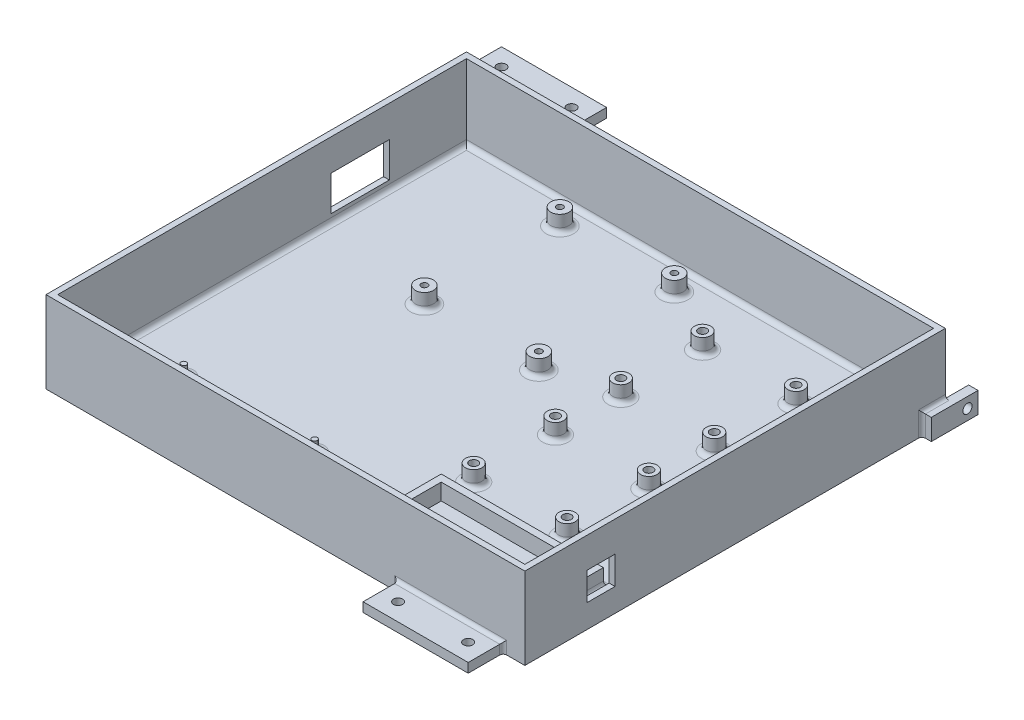
SolidWorks part; units mm, degrees
ref_plane "Front Plane" through (0, 0, 0) normal (0, 0, 1) x (1, 0, 0)
ref_plane "Top Plane" through (0, 0, 0) normal (0, 1, 0) x (1, 0, 0)
ref_plane "Right Plane" through (0, 0, 0) normal (1, 0, 0) x (0, 0, -1)
other "Configuration Table"
sketch "Sketch1" plane through (0, 0, 0) normal (0, 1, 0) x (1, 0, 0)
  line L1 (100, -87.5) -> (-100, -87.5)
  line L2 (100, -87.5) -> (100, 87.5)
  line L3 (100, 87.5) -> (-100, 87.5)
  line L4 (-100, -87.5) -> (-100, 87.5)
  line L5 (100, -87.5) -> (-100, 87.5) construction
  line L6 (100, 87.5) -> (-100, -87.5) construction
  point P0 (0, 0)
  dimension "D1" = 175
  dimension "D2" = 200
extrude "Boss-Extrude1" add sketch "Sketch1" along normal blind 3
sketch "Sketch2" plane through (0, 3, 0) normal (0, 1, 0) x (1, 0, 0)
  line L0 (-100, -87.5) -> (100, -87.5) construction
  line L1 (26.6, -49.9) -> (90, -49.9)
  line L2 (26.6, -49.9) -> (26.6, -77.5)
  line L3 (26.6, -77.5) -> (90, -77.5)
  line L4 (90, -49.9) -> (90, -77.5)
  line L5 (26.6, -49.9) -> (90, -77.5) construction
  line L6 (26.6, -77.5) -> (90, -49.9) construction
  line L7 (100, -87.5) -> (100, 87.5) construction
  line L8 (23.6, -46.9) -> (23.6, -80.5)
  line L9 (23.6, -80.5) -> (93, -80.5)
  line L10 (93, -46.9) -> (93, -80.5)
  line L11 (23.6, -46.9) -> (93, -46.9)
  point P0 (58.3, -63.7)
  dimension "D1" = 27.6
  dimension "D2" = 63.4
  dimension "D3" = 10
  dimension "D4" = 10
  dimension "D5" = 3
extrude "Boss-Extrude2" add sketch "Sketch2" along normal blind 7
sketch "Sketch3" plane through (0, 3, 0) normal (0, 1, 0) x (1, 0, 0)
  line L0 (26.5, -0.9) -> (66.5, -35.9) construction
  line L1 (26.5, -35.9) -> (66.5, -0.9) construction
  line L3 (70, -39.9) -> (23, -39.9) construction
  line L4 (70, -39.9) -> (70, 3.1) construction
  line L5 (70, 3.1) -> (23, 3.1) construction
  line L6 (23, -39.9) -> (23, 3.1) construction
  line L7 (70, -39.9) -> (23, 3.1) construction
  line L8 (70, 3.1) -> (23, -39.9) construction
  line L9 (100, -87.5) -> (100, 87.5) construction
  line L10 (100, 13.1) -> (-23, 13.1) construction
  line L11 (93, -46.9) -> (23.6, -46.9) construction
  circle A0 centre (26.5, -35.9) radius 1.8182
  circle A1 centre (66.5, -35.9) radius 1.8182
  circle A2 centre (66.5, -0.9) radius 1.8182
  circle A3 centre (26.5, -0.9) radius 1.8182
  circle A4 centre (26.5, -0.9) radius 3.5
  circle A5 centre (26.5, -35.9) radius 3.5
  circle A6 centre (66.5, -0.9) radius 3.5
  circle A7 centre (66.5, -35.9) radius 3.5
  circle A8 centre (66.5, 27.1) radius 3.5
  circle A9 centre (66.5, 27.1) radius 1.8182
  circle A10 centre (26.5, 62.1) radius 1.8182
  circle A11 centre (66.5, 62.1) radius 3.5
  circle A12 centre (66.5, 62.1) radius 1.8182
  circle A13 centre (26.5, 62.1) radius 3.5
  circle A14 centre (26.5, 27.1) radius 1.8182
  circle A15 centre (26.5, 27.1) radius 3.5
  point P8 (46.5, -18.4)
  dimension "D1" = 3.6364
  dimension "D3" = 35
  dimension "D2" = 40
  dimension "D4" = 47
  dimension "D5" = 43
  dimension "D6" = 30
  dimension "D7" = 10
  dimension "D8" = 7
extrude "Boss-Extrude3" add sketch "Sketch3" along normal blind 7
sketch "Sketch4" plane through (0, 3, 0) normal (0, 1, 0) x (1, 0, 0)
  line L0 (-100, 87.5) -> (-100, -87.5) construction
  line L1 (100, 87.5) -> (-100, 87.5) construction
  circle A0 centre (-50, 77.5) radius 1.3636
  circle A1 centre (-1, 77.5) radius 1.3636
  circle A2 centre (-1, 19.5) radius 1.3636
  circle A3 centre (-50, 19.5) radius 1.3636
  circle A4 centre (-50, 77.5) radius 3.8636
  circle A5 centre (-1, 77.5) radius 3.8636
  circle A6 centre (-1, 19.5) radius 3.8636
  circle A7 centre (-50, 19.5) radius 3.8636
  point P24 (26.5, 77.5)
  dimension "D1" = 2.7273
  dimension "D2" = 58
  dimension "D3" = 49
  dimension "D5" = 50
  dimension "D6" = 10
  dimension "D4" = 2.5
extrude "Boss-Extrude4" add sketch "Sketch4" along normal blind 7
sketch "Sketch6" plane through (0, 0, 0) normal (0, -1, 0) x (1, 0, 0)
  line L4 (-100, 87.5) -> (-100, -87.5)
  line L5 (-100, -87.5) -> (100, -87.5)
  line L6 (100, -87.5) -> (100, 87.5)
  line L7 (100, 87.5) -> (-100, 87.5)
  line L8 (-100, 87.5) -> (-100, -87.5)
  line L9 (-100, -87.5) -> (100, -87.5)
  line L10 (100, -87.5) -> (100, 87.5)
  line L11 (100, 87.5) -> (-100, 87.5)
  line L16 (-102.5, 90) -> (-102.5, -90)
  line L17 (-102.5, -90) -> (102.5, -90)
  line L18 (102.5, -90) -> (102.5, 90)
  line L19 (102.5, 90) -> (-102.5, 90)
  line L20 (-102.5, 90) -> (-102.5, -90)
  line L21 (-102.5, -90) -> (102.5, -90)
  line L22 (102.5, -90) -> (102.5, 90)
  line L23 (102.5, 90) -> (-102.5, 90)
  dimension "D1" = 0
  dimension "D2" = 2.5
extrude "Boss-Extrude5" add sketch "Sketch6" against normal blind 35
fillet "Fillet1" radius 2 20 edges at (58.3, 3, 80.5) (93, 3, 63.7) (58.3, 3, 46.9) (23.6, 3, 63.7) (0, 3, -87.5) (100, 3, 0) (0, 3, 87.5) (-100, 3, 0) (26.5, 3, 39.4) (26.5, 3, 4.4) (66.5, 3, 4.4) (66.5, 3, 39.4) (66.5, 3, -30.6) (66.5, 3, -65.6) (26.5, 3, -65.6) (26.5, 3, -30.6) (-50, 3, -73.6364) (-1, 3, -73.6364) (-1, 3, -15.6364) (-50, 3, -15.6364)
sketch "Sketch7" plane through (100, 0, 0) normal (-1, 0, 0) x (0, 0, 1)
  line L1 (51.4, 10) -> (63.4, 10)
  line L2 (51.4, 10) -> (51.4, 22)
  line L3 (51.4, 22) -> (63.4, 22)
  line L4 (63.4, 10) -> (63.4, 22)
  line L13 (49.9, 10) -> (49.9, 3) construction
  line L14 (77.5, 10) -> (49.9, 10) construction
  line L15 (49.9, 10) -> (49.9, 3) construction
  line L16 (77.5, 10) -> (49.9, 10) construction
  point P10 (57.4, 22)
  dimension "D1" = 12
  dimension "D2" = 7.5
  dimension "D3" = 12
extrude "Cut-Extrude1" cut sketch "Sketch7" against normal through all
sketch "Sketch8" plane through (0, 3, 0) normal (0, 1, 0) x (1, 0, 0)
  line L0 (100, -87.5) -> (-100, -87.5) construction
  line L1 (23.6, -46.9) -> (23.6, -80.5) construction
  line L2 (-100, -87.5) -> (-100, 87.5) construction
  circle A0 centre (-19, -58.5) radius 1.1364
  circle A1 centre (-75, -58.5) radius 1.1364
  circle A2 centre (-75, -77.5) radius 1.1364
  circle A3 centre (-19, -77.5) radius 1.1364
  dimension "D1" = 2.2727
  dimension "D2" = 10
  dimension "D3" = 42.6
  dimension "D4" = 56
  dimension "D5" = 19
  dimension "D6" = 25
extrude "Boss-Extrude6" add sketch "Sketch8" along normal blind 4.5
fillet "Fillet2" radius 3 4 edges at (-19, 3, 78.6364) (-19, 3, 59.6364) (-75, 3, 78.6364) (-75, 3, 59.6364)
sketch "Sketch9" plane through (-102.5, 0, 0) normal (-1, 0, 0) x (0, 0, 1)
  line L0 (-90, 35) -> (-90, 0) construction
  line L1 (-54.5, 6.5) -> (-29.5, 6.5)
  line L2 (-54.5, 6.5) -> (-54.5, 21.5)
  line L3 (-54.5, 21.5) -> (-29.5, 21.5)
  line L4 (-29.5, 6.5) -> (-29.5, 21.5)
  line L5 (-54.5, 6.5) -> (-29.5, 21.5) construction
  line L6 (-54.5, 21.5) -> (-29.5, 6.5) construction
  line L7 (90, 0) -> (-90, 0) construction
  point P0 (-42, 14)
  dimension "D1" = 48
  dimension "D2" = 14
  dimension "D3" = 15
  dimension "D4" = 25
extrude "Cut-Extrude2" cut sketch "Sketch9" against normal blind 10
sketch "Sketch10" plane through (102.5, 0, 0) normal (1, 0, 0) x (0, 0, -1)
  line L0 (90, 0) -> (-90, 0) construction
  line L1 (80, 9) -> (100, 9)
  line L2 (80, 9) -> (80, 0)
  line L3 (80, 0) -> (100, 0)
  line L4 (100, 9) -> (100, 0)
  line L6 (90, 35) -> (90, 0) construction
  circle A2 centre (95.5, 4.5) radius 1.985
  point P11 (100, 4.5)
  dimension "D5" = 3.97
  dimension "D1" = 9
  dimension "D2" = 10
  dimension "D3" = 4.5
  dimension "D4" = 10
extrude "Boss-Extrude7" add sketch "Sketch10" along normal blind 4
sketch "Sketch11" plane through (0, 0, 0) normal (0, -1, 0) x (1, 0, 0)
  line L0 (102.5, 90) -> (-102.5, 90) construction
  line L1 (48.25, 90) -> (93.25, 90)
  line L2 (48.25, 90) -> (48.25, 105)
  line L3 (48.25, 105) -> (93.25, 105)
  line L4 (93.25, 90) -> (93.25, 105)
  line L5 (102.5, 90) -> (39, 90) construction
  line L6 (55.75, 97.5) -> (85.75, 97.5) construction
  circle A0 centre (55.75, 97.5) radius 1.985
  circle A1 centre (85.75, 97.5) radius 1.985
  point P9 (70.75, 90)
  point P14 (70.75, 97.5)
  dimension "D5" = 3.97
  dimension "D1" = 63.5
  dimension "D2" = 15
  dimension "D3" = 45
  dimension "D4" = 7.5
  dimension "D6" = 7.5
extrude "Boss-Extrude8" add sketch "Sketch11" against normal blind 4
sketch "Sketch12" plane through (0, 0, 0) normal (0, -1, 0) x (1, 0, 0)
  line L0 (-102.5, -90) -> (102.5, -90) construction
  line L1 (-102.5, -90) -> (-57.5, -90)
  line L2 (-102.5, -90) -> (-102.5, -105)
  line L3 (-102.5, -105) -> (-57.5, -105)
  line L4 (-57.5, -90) -> (-57.5, -105)
  line L5 (-278.5, -90) -> (102.5, -90) construction
  line L6 (-95, -97.5) -> (-65, -97.5) construction
  line L7 (-102.5, 90) -> (-102.5, -90) construction
  circle A0 centre (-95, -97.5) radius 1.985
  circle A1 centre (-65, -97.5) radius 1.985
  point P12 (-80, -97.5)
  point P13 (-80, -105)
  point P16 (-102.5, -97.5)
  dimension "D3" = 3.97
  dimension "D1" = 45
  dimension "D2" = 15
  dimension "D4" = 30
extrude "Boss-Extrude9" add sketch "Sketch12" against normal blind 4 from offset 25.4 offset against normal yes
fillet "Fillet3" radius 1.5 7 edges at (-57.5, 27.4, -90) (102.5, 4.5, -80) (102.5, 9, -85) (93.25, 2, 90) (70.75, 4, 90) (48.25, 2, 90) (-80, 29.4, -90)
